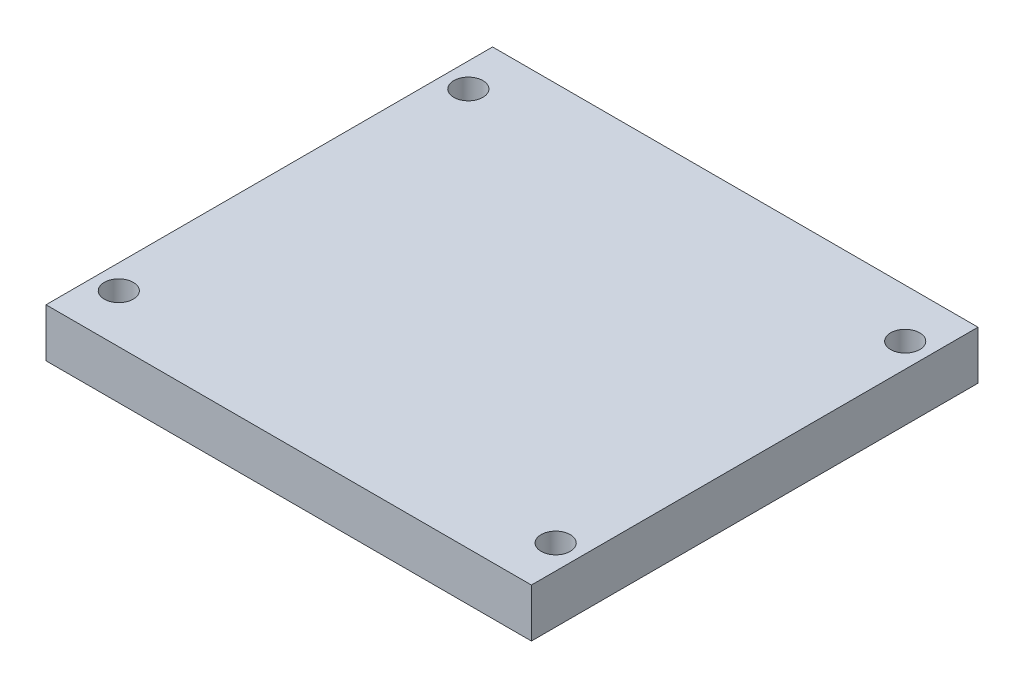
SolidWorks part; units mm, degrees
ref_plane "Front Plane" through (0, 0, 0) normal (0, 0, 1) x (1, 0, 0)
ref_plane "Top Plane" through (0, 0, 0) normal (0, 1, 0) x (1, 0, 0)
ref_plane "Right Plane" through (0, 0, 0) normal (1, 0, 0) x (0, 0, -1)
sketch "Sketch1" plane through (0, 0, 0) normal (0, 1, 0) x (1, 0, 0)
  line L1 (0, 0) -> (25, 0)
  line L2 (0, 0) -> (0, 46)
  line L3 (0, 46) -> (25, 46)
  line L4 (25, 0) -> (25, 46)
  circle A0 centre (22.5, 5) radius 1.5
  circle A1 centre (22.5, 41) radius 1.5
  dimension "D3" = 3
  dimension "D4" = 3
  dimension "D1" = 25
  dimension "D2" = 46
  dimension "D5" = 2.5
  dimension "D6" = 2.5
  dimension "D7" = 5
  dimension "D8" = 5
extrude "Boss-Extrude1" add sketch "Sketch1" along normal blind 5
mirror "Mirror1" about plane through (0, 5, 0) normal (1, 0, 0) of "Boss-Extrude1"
